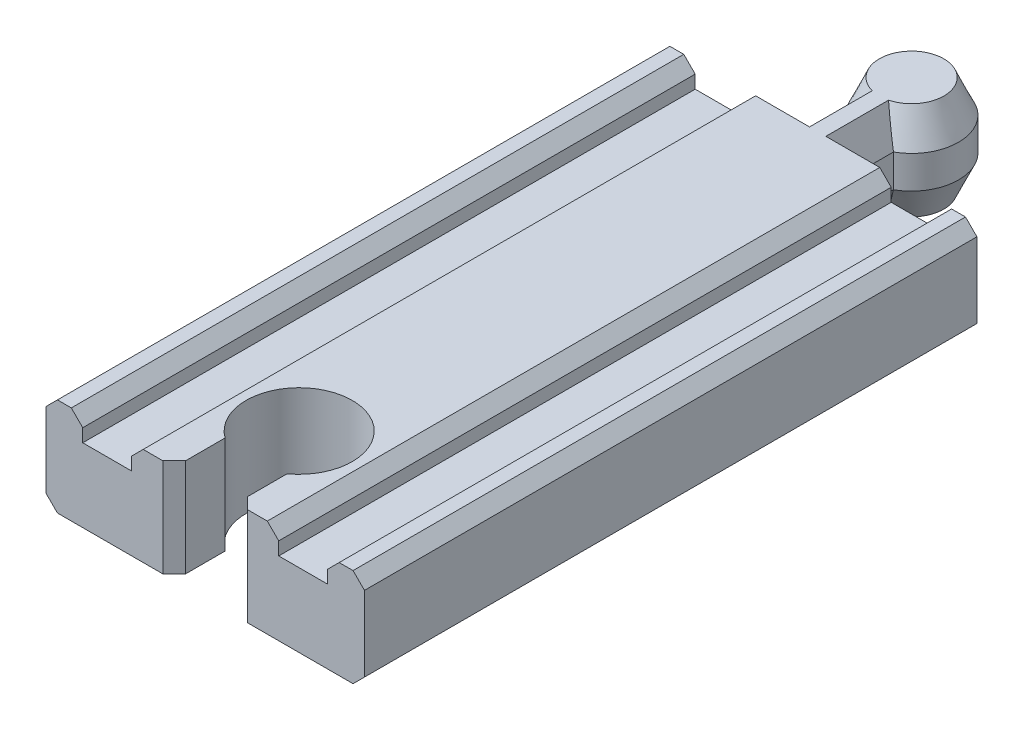
SolidWorks part; units mm, degrees
ref_plane "Front Plane" through (0, 0, 0) normal (0, 0, 1) x (1, 0, 0)
ref_plane "Top Plane" through (0, 0, 0) normal (0, 1, 0) x (1, 0, 0)
ref_plane "Right Plane" through (0, 0, 0) normal (1, 0, 0) x (0, 0, -1)
sketch "Sketch2" plane through (0, 0, 0) normal (0, 0, 1) x (1, 0, 0)
  line L0 (-19.5, 0) -> (19.5, 0)
  line L1 (19.5, 0) -> (19.5, 12)
  line L2 (19.5, 12) -> (15, 12)
  line L3 (15, 12) -> (15, 9)
  line L4 (15, 9) -> (9, 9)
  line L5 (9, 9) -> (9, 12)
  line L6 (9, 12) -> (-9, 12)
  line L7 (-9, 12) -> (-9, 9)
  line L8 (-9, 9) -> (-15, 9)
  line L9 (-15, 9) -> (-15, 12)
  line L10 (-15, 12) -> (-19.5, 12)
  line L11 (-19.5, 12) -> (-19.5, 0)
  point P4 (0, 0)
  point P14 (0, 0)
  dimension "D1" = 39
  dimension "D2" = 12
  dimension "D3" = 3
  dimension "D4" = 4.5
  dimension "D5" = 6
extrude "Boss-Extrude1" add sketch "Sketch2" along normal mid plane 75
sketch "Sketch3" plane through (0, 12, 0) normal (0, 1, 0) x (1, 0, 0)
  line L0 (9, -37.5) -> (-9, -37.5) construction
  line L2 (3.8, -37.5) -> (-3.8, -37.5)
  line L3 (3.8, -37.5) -> (3.8, -26)
  line L4 (3.8, -26) -> (-3.8, -26)
  line L5 (-3.8, -37.5) -> (-3.8, -26)
  line L6 (3.8, -37.5) -> (-3.8, -26) construction
  line L7 (3.8, -26) -> (-3.8, -37.5) construction
  circle A0 centre (0, -26) radius 6.5
  point P4 (0, -31.75)
  point P5 (0, 0)
  point P11 (0, 0)
  line M1 (-9, -37.5) -> (9, -37.5)
  dimension "D1" = 13
  dimension "D2" = 11.5
  dimension "D3" = 7.6
extrude "Cut-Extrude1" cut sketch "Sketch3" against normal through all contours L5 A0 L3 L4 | L3 A0 L5 L4 | A0 L5 L3 M1
chamfer "Chamfer1" distance 1.4 10 edges at (19.5, 0, 0) (19.5, 12, 0) (15, 12, 0) (9, 12, 0) (-9, 12, 0) (-19.5, 0, 0) (-19.5, 12, 0) (-15, 12, 0) (3.8, 6, 37.5) (-3.8, 6, 37.5)
sketch "Sketch4" plane through (0, 12, 0) normal (0, 1, 0) x (1, 0, 0)
  line L0 (7.6, 37.5) -> (-7.6, 37.5) construction
  line L1 (-2.8, 49) -> (2.8, 49)
  line L2 (-2.8, 49) -> (-2.8, 37.5)
  line L3 (-2.8, 37.5) -> (2.8, 37.5)
  line L4 (2.8, 49) -> (2.8, 37.5)
  line L5 (-2.8, 49) -> (2.8, 37.5) construction
  line L6 (-2.8, 37.5) -> (2.8, 49) construction
  circle A0 centre (0, 49) radius 5.75
  point P2 (0, 43.25)
  point P9 (0, 0)
  point P11 (0, 0)
  point P12 (0, 0)
  line M9 (7.6, 37.5) -> (-7.6, 37.5)
  dimension "D1" = 11.5
  dimension "D2" = 5.6
  dimension "D3" = 11.5
extrude "Boss-Extrude2" add sketch "Sketch4" against normal up to surface (12 mm away) contours L2 A0 L4 L1 | A0 L2 L4 M9 | L4 A0 L2 L1 up to face at (0, 0, 19.7974)
chamfer "Chamfer2" distance 4 distance2 1.8 6 edges at (0, 0, -54.75) (0, 12, -54.75) (-2.8, 0, -40.7389) (-2.8, 12, -40.7389) (2.8, 0, -40.7389) (2.8, 12, -40.7389)
